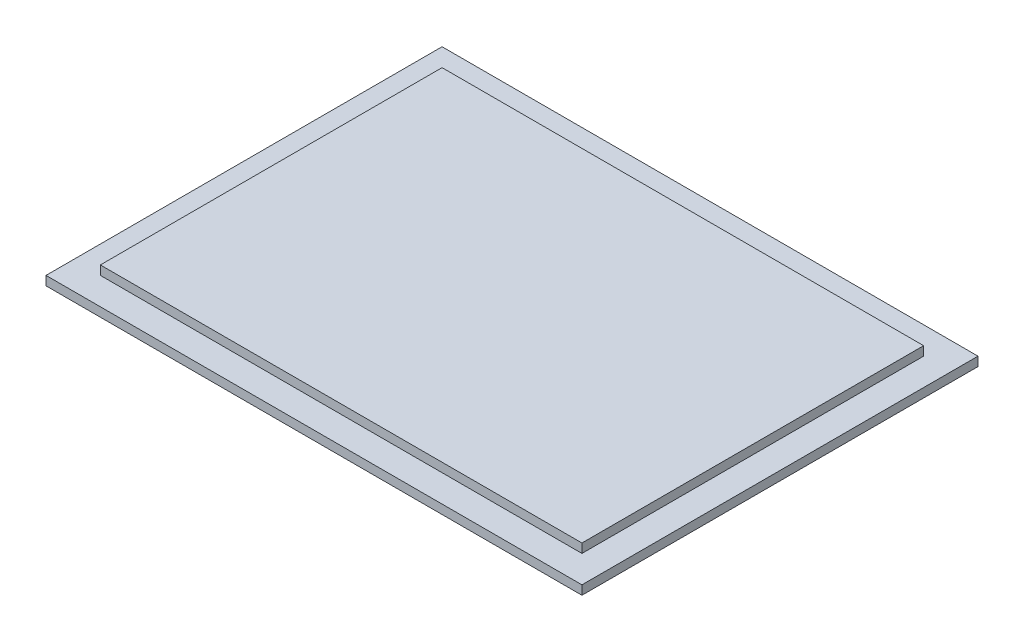
SolidWorks part; units mm, degrees
ref_plane "Front Plane" through (0, 0, 0) normal (0, 0, 1) x (1, 0, 0)
ref_plane "Top Plane" through (0, 0, 0) normal (0, 1, 0) x (1, 0, 0)
ref_plane "Right Plane" through (0, 0, 0) normal (1, 0, 0) x (0, 0, -1)
sketch "Sketch1" plane through (0, 0, 0) normal (0, 1, 0) x (1, 0, 0)
  line L1 (-26.58, 18.86) -> (26.58, 18.86)
  line L2 (-26.58, 18.86) -> (-26.58, -18.86)
  line L3 (-26.58, -18.86) -> (26.58, -18.86)
  line L4 (26.58, 18.86) -> (26.58, -18.86)
  line L5 (-26.58, 18.86) -> (26.58, -18.86) construction
  line L6 (-26.58, -18.86) -> (26.58, 18.86) construction
  point P0 (0, 0)
extrude "Boss-Extrude1" add sketch "Sketch1" along normal blind 1
sketch "Sketch2" plane through (0, 0, 0) normal (0, -1, 0) x (1, 0, 0)
  line L0 (29.58, -21.86) -> (29.58, 21.86)
  line L1 (29.58, 21.86) -> (-29.58, 21.86)
  line L2 (-29.58, 21.86) -> (-29.58, -21.86)
  line L3 (-29.58, -21.86) -> (29.58, -21.86)
  line L4 (26.58, -18.86) -> (26.58, 18.86)
  line L5 (26.58, 18.86) -> (-26.58, 18.86)
  line L6 (-26.58, 18.86) -> (-26.58, -18.86)
  line L7 (-26.58, -18.86) -> (26.58, -18.86)
  line L8 (26.58, -18.86) -> (26.58, 18.86)
  line L9 (26.58, 18.86) -> (-26.58, 18.86)
  line L10 (-26.58, 18.86) -> (-26.58, -18.86)
  line L11 (-26.58, -18.86) -> (26.58, -18.86)
  dimension "D1" = 0
  dimension "D2" = 3
extrude "Boss-Extrude2" add sketch "Sketch2" along normal blind 1 separate body
